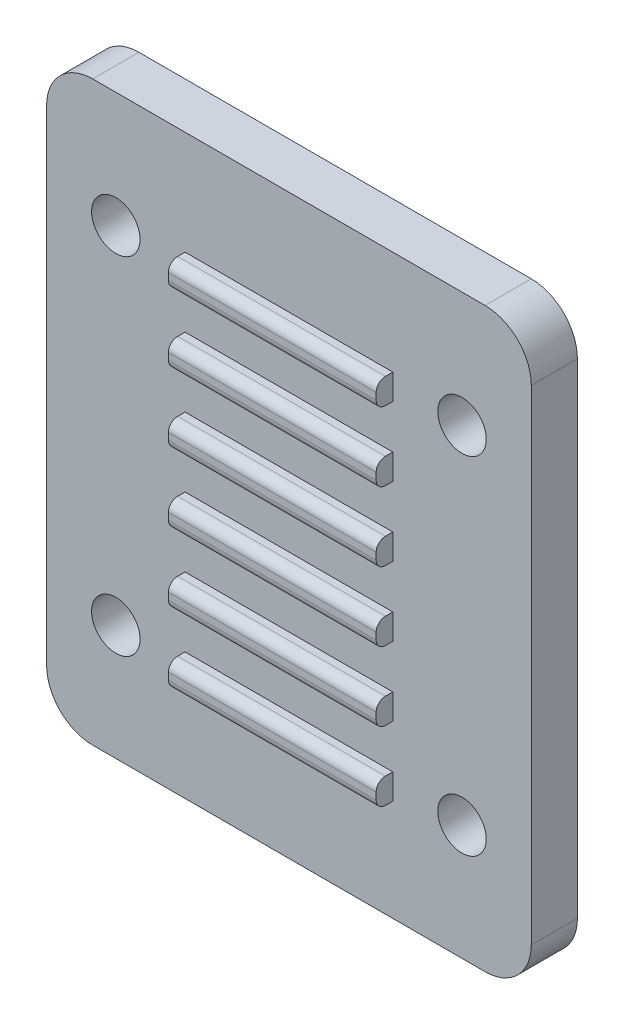
SolidWorks part; units mm, degrees
ref_plane "前视基准面" through (0, 0, 0) normal (0, 0, 1) x (1, 0, 0)
ref_plane "上视基准面" through (0, 0, 0) normal (0, 1, 0) x (1, 0, 0)
ref_plane "右视基准面" through (0, 0, 0) normal (1, 0, 0) x (0, 0, -1)
sketch "草图1" plane through (0, 0, 0) normal (0, 0, 1) x (1, 0, 0)
  line L1 (0, 0) -> (21, 0)
  line L2 (0, 0) -> (0, -25)
  line L3 (0, -25) -> (21, -25)
  line L4 (21, 0) -> (21, -25)
  circle A0 centre (3, -5) radius 1.05
  circle A1 centre (18, -5) radius 1.05
  circle A2 centre (3, -20) radius 1.05
  circle A3 centre (18, -20) radius 1.05
  dimension "D3" = 2
  dimension "D5" = 15
  dimension "D6" = 15
  dimension "D1" = 21
  dimension "D2" = 25
  dimension "D7" = 5
  dimension "D8" = 3
  dimension "D4" = 2
extrude "凸台-拉伸1" add sketch "草图1" along normal blind 2
sketch "草图2" plane through (0, 0, 2) normal (0, 0, 1) x (1, 0, 0)
  line L0 (21, 0) -> (0, 0) construction
  line L1 (6, -4.5) -> (15, -4.5)
  line L2 (6, -4.5) -> (6, -5.6)
  line L3 (6, -5.6) -> (15, -5.6)
  line L4 (15, -4.5) -> (15, -5.6)
  line L5 (0, 0) -> (0, -25) construction
  line L6 (6, -7.5) -> (6, -8.6)
  line L7 (6, -7.5) -> (15, -7.5)
  line L8 (15, -7.5) -> (15, -8.6)
  line L9 (6, -8.6) -> (15, -8.6)
  line L10 (6, -10.5) -> (6, -11.6)
  line L11 (6, -10.5) -> (15, -10.5)
  line L12 (15, -10.5) -> (15, -11.6)
  line L13 (6, -11.6) -> (15, -11.6)
  line L14 (6, -13.5) -> (6, -14.6)
  line L15 (6, -13.5) -> (15, -13.5)
  line L16 (15, -13.5) -> (15, -14.6)
  line L17 (6, -14.6) -> (15, -14.6)
  line L18 (6, -16.5) -> (6, -17.6)
  line L19 (6, -16.5) -> (15, -16.5)
  line L20 (15, -16.5) -> (15, -17.6)
  line L21 (6, -17.6) -> (15, -17.6)
  line L22 (6, -19.5) -> (6, -20.6)
  line L23 (6, -19.5) -> (15, -19.5)
  line L24 (15, -19.5) -> (15, -20.6)
  line L25 (6, -20.6) -> (15, -20.6)
  dimension "D1" = 4.5
  dimension "D2" = 6
  dimension "D3" = 9
  dimension "D4" = 1.1
  dimension "D5" = 6
extrude "凸台-拉伸2" add sketch "草图2" along normal blind 0.72
fillet "圆角1" radius 2 4 edges at (21, 0, 1) (21, -25, 1) (0, -25, 1) (0, 0, 1)
fillet "圆角3" radius 0.4 12 edges at (10.5, -5.6, 2.72) (10.5, -4.5, 2.72) (10.5, -8.6, 2.72) (10.5, -7.5, 2.72) (10.5, -11.6, 2.72) (10.5, -10.5, 2.72) (10.5, -14.6, 2.72) (10.5, -13.5, 2.72) (10.5, -17.6, 2.72) (10.5, -16.5, 2.72) (10.5, -20.6, 2.72) (10.5, -19.5, 2.72)
